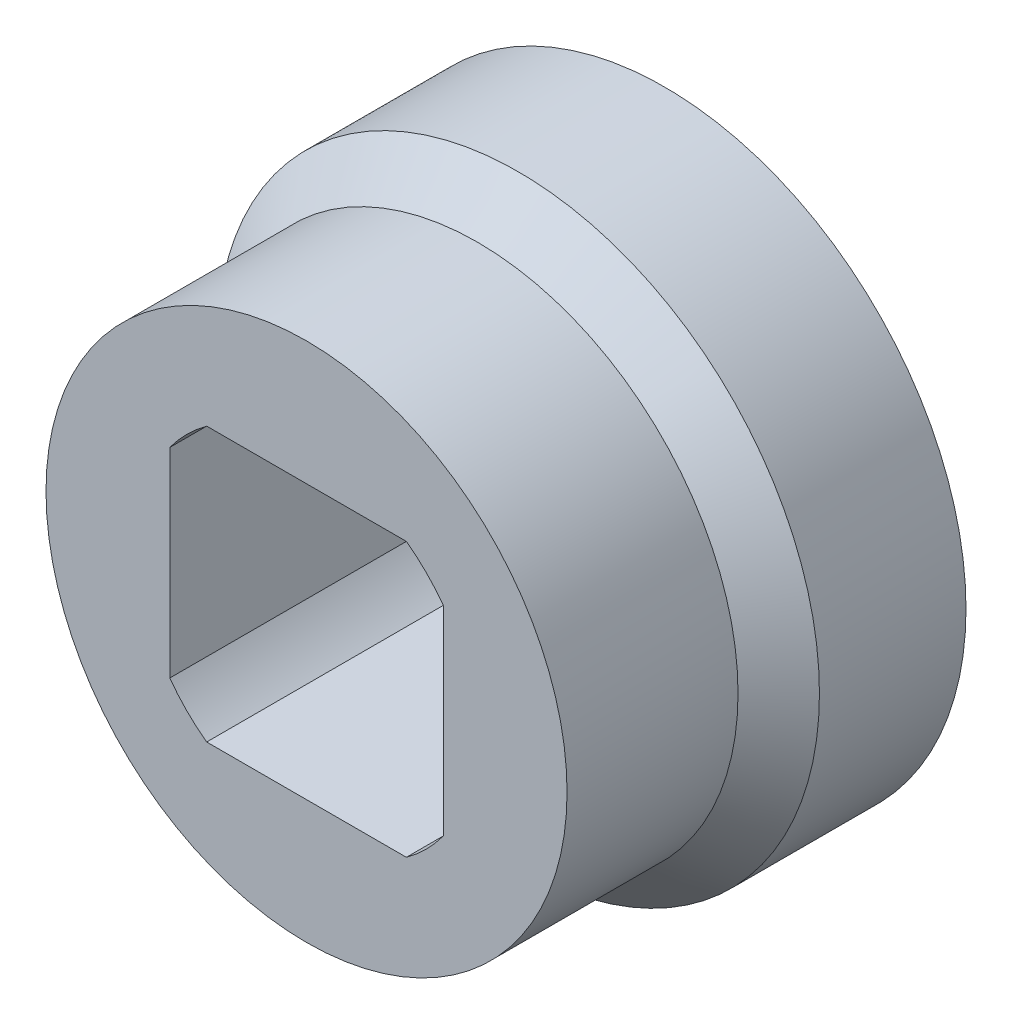
SolidWorks part; units mm, degrees
material "ABS generico"
ref_plane "Piano frontale" through (0, 0, 0) normal (0, 0, 1) x (1, 0, 0)
ref_plane "Piano superiore" through (0, 0, 0) normal (0, 1, 0) x (1, 0, 0)
ref_plane "Piano destro" through (0, 0, 0) normal (1, 0, 0) x (0, 0, -1)
ref_plane "Piano1" through (0, 0, 0) normal (0, -1, 0) x (1, 0, 0)
sketch "Schizzo1" plane through (0, 0, 0) normal (0, -1, 0) x (1, 0, 0)
  line L0 (16, -3.5) -> (0, -3.5)
  line L1 (0, -3.5) -> (0, -25.5)
  line L2 (0, -25.5) -> (18.5, -25.5)
  line L3 (18.5, -25.5) -> (18.5, -16.5)
  line L4 (18.5, -16.5) -> (16, -14)
  line L5 (16, -14) -> (16, -3.5)
  line L6 (0, -3.5) -> (0, -25.5) construction
  dimension "D1" = 16
  dimension "D2" = 18.5
  dimension "D3" = 9
  dimension "D4" = 11.5
  dimension "D5" = 22
revolve "Rivoluzione1" add sketch "Schizzo1" angle 360 about L6
sketch "Schizzo2" plane through (0, 0, -25.5) normal (0, 0, -1) x (-1, 0, 0)
  line L0 (8.4, -6.1319) -> (8.4, 6.1319)
  line L1 (6.1319, 8.4) -> (-6.1319, 8.4)
  line L2 (-8.4, 6.1319) -> (-8.4, -6.1319)
  line L3 (-6.1319, -8.4) -> (6.1319, -8.4)
  arc A0 (8.4, 6.1319) -> (6.1319, 8.4) centre (0, 0) ccw
  arc A1 (-6.1319, 8.4) -> (-8.4, 6.1319) centre (0, 0) ccw
  arc A2 (-8.4, -6.1319) -> (-6.1319, -8.4) centre (0, 0) ccw
  arc A3 (6.1319, -8.4) -> (8.4, -6.1319) centre (0, 0) ccw
  circle A4 centre (0, 0) radius 18.5 construction
  dimension "D1" = 10.4
  dimension "D2" = 10.4
  dimension "D3" = 10.4
  dimension "D4" = 6.1319
  dimension "D5" = 8.4
  dimension "D6" = 6.1319
  dimension "D7" = 6.1319
extrude "Taglio-Estrusione1" cut sketch "Schizzo2" against normal through all
sketch "Schizzo3" plane through (0, 0, 0) normal (0, 1, 0) x (1, 0, 0)
  line L0 (16.3, 25.5) -> (0, 25.5)
  line L1 (0, 25.5) -> (0, 23.5)
  line L2 (0, 23.5) -> (16.3, 23.5)
  line L3 (16.3, 23.5) -> (16.3, 25.5)
  line L4 (0, 25.5) -> (0, 23.5) construction
  dimension "D1" = 16.3
  dimension "D2" = 2
revolve "Taglia-Rivoluzione1" cut sketch "Schizzo3" angle 360 about L4
hole_wizard "Foro Ø4.0 (4)-1" positions "Schizzo5" profile "Schizzo4" hole size "Ø4.0" standard "Ansi Metric"
sketch "Schizzo5" plane through (0, 0, -23.5) normal (0, 0, -1) x (-1, 0, 0)
  point P0 (-12, 0)
  point P1 (0, -12)
  point P2 (12, 0)
  point P3 (0, 12)
sketch "Schizzo4" plane through (12, 0, -23.5) normal (1, 0, 0) x (0, 1, 0)
  line L0 (0, 0) -> (0, 8)
  line L1 (0, 8) -> (2, 8)
  line L2 (2, 8) -> (2, 0)
  line L5 (2, 0) -> (0, 0)
  line L10 (0, 8) -> (-2, 8) construction
  line L11 (0, -6.35) -> (0, 107.95) construction
  dimension "Hole Dia." = 4
  dimension "Hole Depth" = 8
  dimension "Drill Angle" = 180
